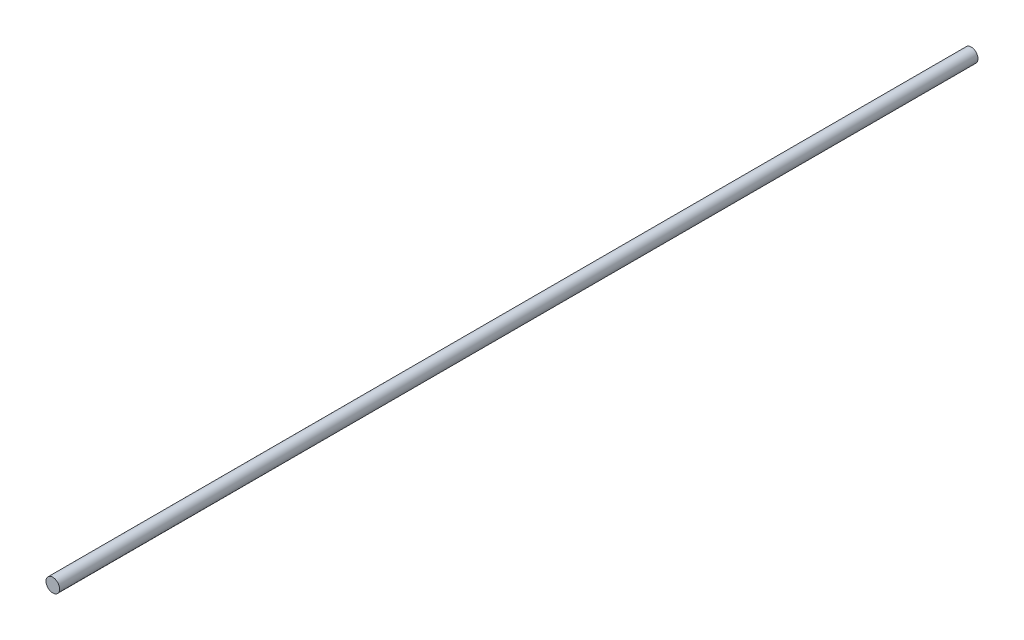
SolidWorks part; units mm, degrees
ref_plane "Front" through (0, 0, 0) normal (0, 0, 1) x (1, 0, 0)
ref_plane "Top" through (0, 0, 0) normal (0, 1, 0) x (1, 0, 0)
ref_plane "Right" through (0, 0, 0) normal (1, 0, 0) x (0, 0, -1)
sketch "Sketch1" plane through (0, 0, 0) normal (0, 0, 1) x (1, 0, 0)
  circle A0 centre (0, 0) radius 4
  dimension "D1" = 8
extrude "Boss-Extrude1" add sketch "Sketch1" along normal blind 540
equation "\"D1@Sketch1\"=8"
equation "\"base-zdepth\" = 500mm"
equation "\"D1@Boss-Extrude1\"=\"base-zdepth\"+40mm"
